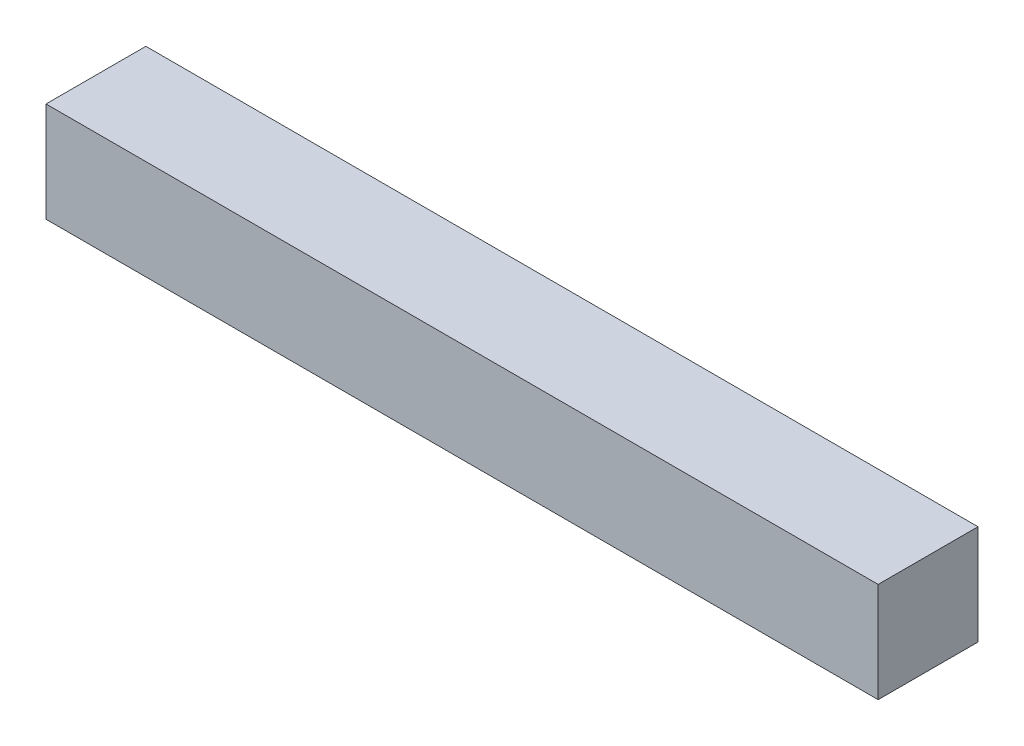
SolidWorks part; units mm, degrees
ref_plane "Front Plane" through (0, 0, 0) normal (0, 0, 1) x (1, 0, 0)
ref_plane "Top Plane" through (0, 0, 0) normal (0, 1, 0) x (1, 0, 0)
ref_plane "Right Plane" through (0, 0, 0) normal (1, 0, 0) x (0, 0, -1)
sketch "Sketch1" plane through (0, 0, 0) normal (1, 0, 0) x (0, 0, -1)
  line L1 (0, 0) -> (38.1, 0)
  line L2 (0, 0) -> (0, -38.1)
  line L3 (0, -38.1) -> (38.1, -38.1)
  line L4 (38.1, 0) -> (38.1, -38.1)
  dimension "D1" = 38.1
  dimension "D2" = 38.1
extrude "Boss-Extrude1" add sketch "Sketch1" along normal blind 317.5
